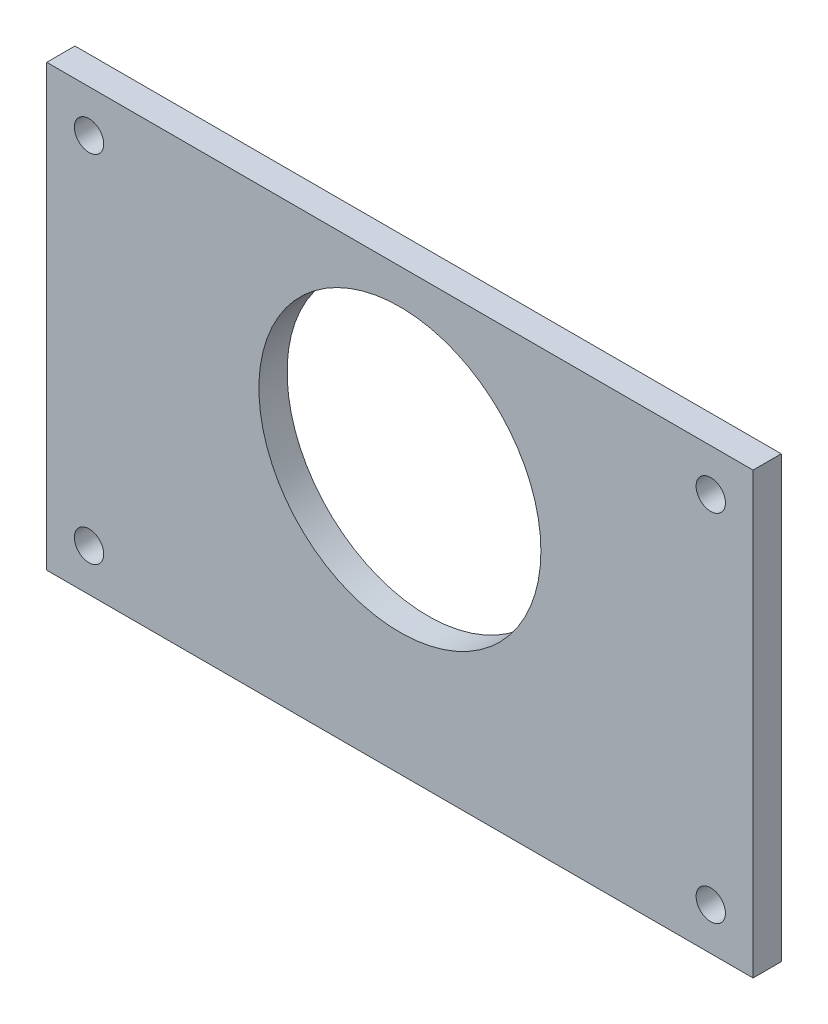
SolidWorks part; units mm, degrees
ref_plane "Front Plane" through (0, 0, 0) normal (0, 0, 1) x (1, 0, 0)
ref_plane "Top Plane" through (0, 0, 0) normal (0, 1, 0) x (1, 0, 0)
ref_plane "Right Plane" through (0, 0, 0) normal (1, 0, 0) x (0, 0, -1)
sketch "Sketch2" plane through (0, 0, 0) normal (0, 0, 1) x (1, 0, 0)
  line L4 (-31.81, -23.7577) -> (31.81, -23.7577)
  line L5 (31.81, -23.7577) -> (31.81, 15.8623)
  line L6 (-31.81, 15.8623) -> (31.81, 15.8623)
  line L7 (-31.81, -23.7577) -> (-31.81, 15.8623)
  circle A4 centre (-28, -19.9477) radius 1.3208
  circle A5 centre (28, -19.9477) radius 1.3208
  circle A6 centre (28, 12.0523) radius 1.3208
  circle A7 centre (-28, 12.0523) radius 1.3208
  circle A8 centre (0, 0) radius 12.7
  point P5 (0, 0)
  point P7 (0, 0)
  point P22 (0, 13.7394)
  point P23 (0, 0)
  point P24 (0, 12.7)
  point P25 (0, 0)
  point P27 (28, -7.4385)
  point P28 (-31.81, 25.5918)
  point P29 (0, 0)
  dimension "D1" = 2.6416
  dimension "D2" = 25.4
  dimension "D3" = 63.62
  dimension "D4" = 39.62
  dimension "D5" = 12.0523
  dimension "D6" = 3.81
  dimension "D7" = 28
  dimension "D8" = 31.81
  dimension "D9" = 28
  dimension "D10" = 32
extrude "Boss-Extrude1" add sketch "Sketch2" along normal blind 2.54
